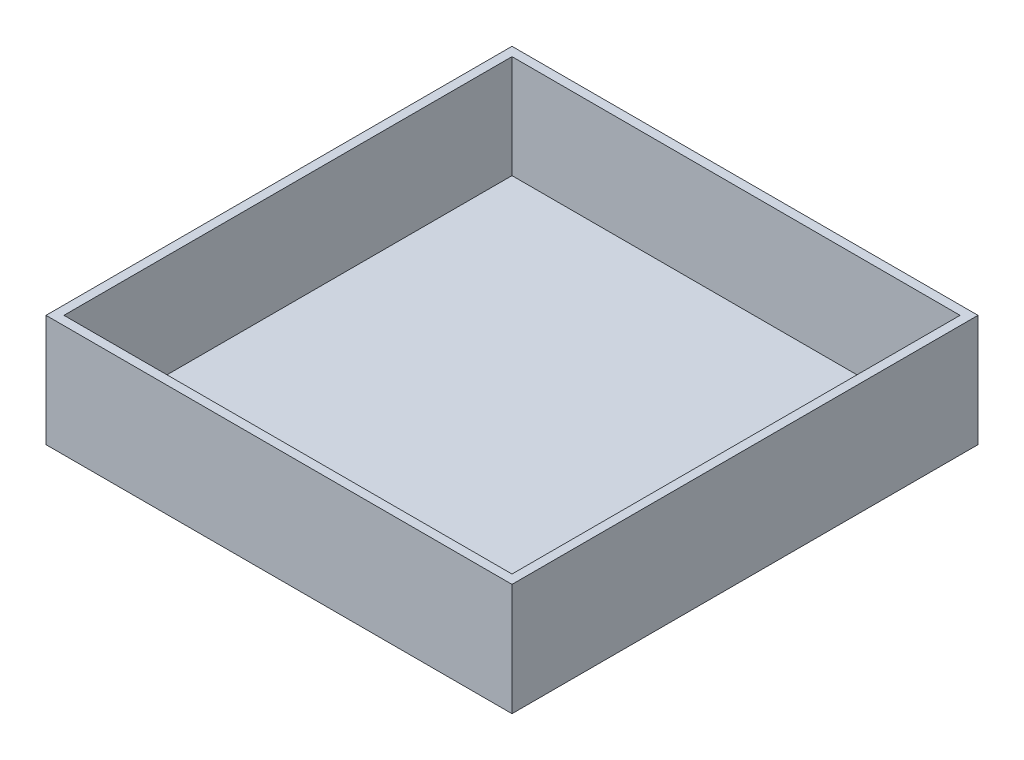
SolidWorks part; units mm, degrees
ref_plane "Front Plane" through (0, 0, 0) normal (0, 0, 1) x (1, 0, 0)
ref_plane "Top Plane" through (0, 0, 0) normal (0, 1, 0) x (1, 0, 0)
ref_plane "Right Plane" through (0, 0, 0) normal (1, 0, 0) x (0, 0, -1)
sketch "Sketch1" plane through (0, 0, 0) normal (0, 1, 0) x (1, 0, 0)
  line L1 (-260, -260) -> (260, -260)
  line L2 (-260, -260) -> (-260, 260)
  line L3 (-260, 260) -> (260, 260)
  line L4 (260, -260) -> (260, 260)
  line L5 (-260, -260) -> (260, 260) construction
  line L6 (-260, 260) -> (260, -260) construction
  point P0 (0, 0)
  dimension "D1" = 520
  dimension "D2" = 520
extrude "Boss-Extrude1" add sketch "Sketch1" along normal blind 125
shell "Shell1" thickness 10
